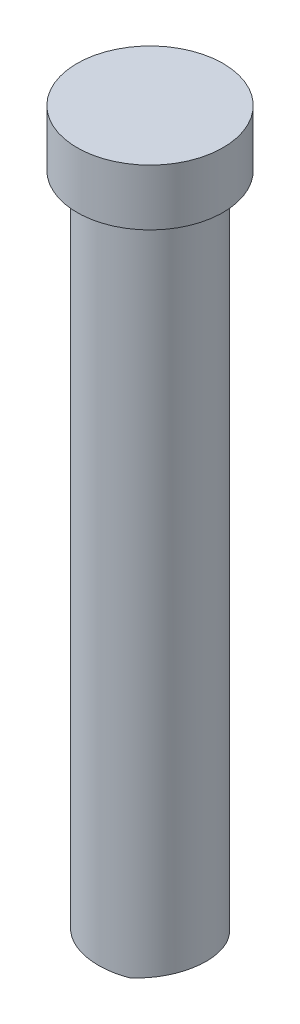
SolidWorks part; units mm, degrees
material "M2 HSS"
ref_plane "Front Plane" through (0, 0, 0) normal (0, 0, 1) x (1, 0, 0)
ref_plane "Top Plane" through (0, 0, 0) normal (0, 1, 0) x (1, 0, 0)
ref_plane "Right Plane" through (0, 0, 0) normal (1, 0, 0) x (0, 0, -1)
sketch "Sketch1" plane through (0, 0, 0) normal (0, 0, 1) x (1, 0, 0)
  line L0 (0, 0) -> (6.5, 0)
  line L1 (6.5, 0) -> (6.5, -5)
  line L2 (6.5, -5) -> (5, -5)
  line L3 (5, -5) -> (5, -64.2)
  line L4 (5, -64.2) -> (0, -64.2)
  line L5 (0, -64.2) -> (0, 0)
  line L6 (0, -69.2) -> (0, 5) construction
  dimension "D1" = 5
  dimension "D2" = 64.2
  dimension "D3" = 5
  dimension "D4" = 5
  dimension "D5" = 10
  dimension "D6" = 13
revolve "Revolve1" add sketch "Sketch1" angle 360 about L6
sketch "Sketch2" plane through (0, 0, 0) normal (0, 0, 1) x (1, 0, 0)
  line L0 (0, -64.2) -> (5, -63.4973)
  line L1 (-5, -64.2) -> (5, -64.2) construction
  line L2 (5, -64.2) -> (5, -5) construction
  line L3 (5, -63.4973) -> (5, -64.2)
  line L4 (5, -64.2) -> (0, -64.2)
  dimension "D1" = 5
  dimension "D2" = 8
  dimension "D3" = 0.7027
extrude "Cut-Extrude1" cut sketch "Sketch2" against normal through all both and the other way through all
pattern_circular "CirPattern1" count 3 over 360 about axis through (0, 0, 0) along (0, 1, 0) of "Cut-Extrude1"
